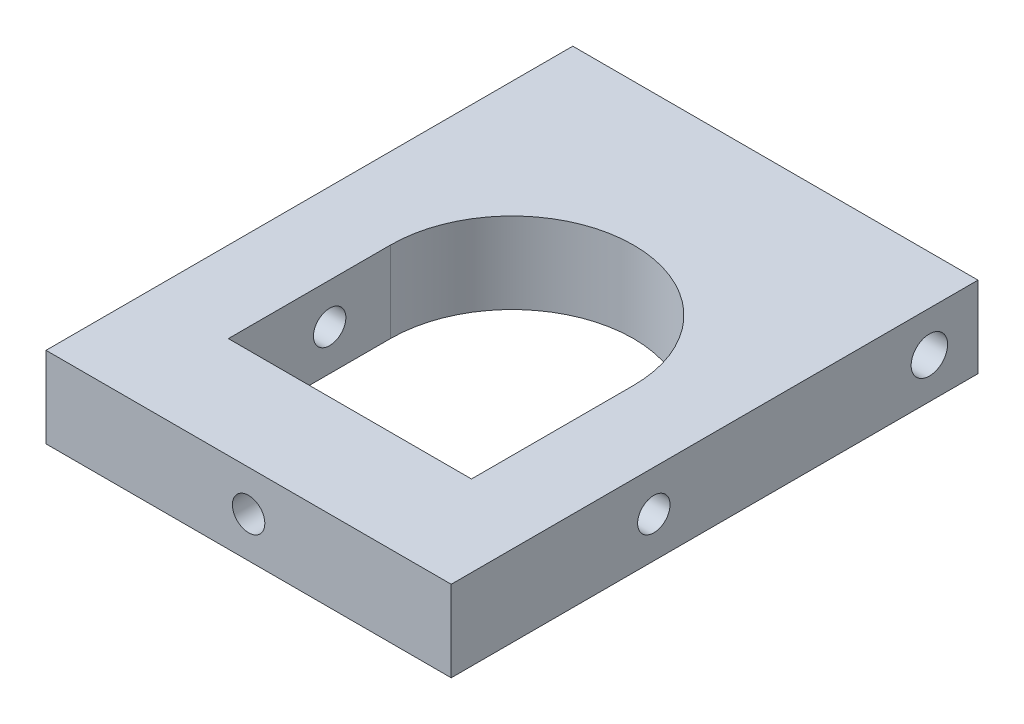
SolidWorks part; units mm, degrees
ref_plane "Front Plane" through (0, 0, 0) normal (0, 0, 1) x (1, 0, 0)
ref_plane "Top Plane" through (0, 0, 0) normal (0, 1, 0) x (1, 0, 0)
ref_plane "Right Plane" through (0, 0, 0) normal (1, 0, 0) x (0, 0, -1)
sketch "Sketch1" plane through (0, 0, 0) normal (0, 1, 0) x (1, 0, 0)
  line L0 (-15, 0) -> (-15, -20)
  line L1 (-25, 32.5) -> (25, 32.5)
  line L2 (-25, 32.5) -> (-25, -32.5)
  line L3 (-25, -32.5) -> (25, -32.5)
  line L4 (25, 32.5) -> (25, -32.5)
  line L5 (-25, 32.5) -> (25, -32.5) construction
  line L6 (-25, -32.5) -> (25, 32.5) construction
  line L7 (-15, -20) -> (15, -20)
  line L8 (15, -20) -> (15, 0)
  arc A0 (15, 0) -> (-15, 0) centre (0, 0) ccw
  point P0 (0, 0)
  dimension "D3" = 30
  dimension "D1" = 50
  dimension "D2" = 65
  dimension "D4" = 20
extrude "Boss-Extrude1" add sketch "Sketch1" along normal blind 10
sketch "Sketch6" plane through (0, 0, 0) normal (1, 0, 0) x (0, 0, -1)
  line L0 (-32.5, 5) -> (32.5, 5) construction
  line L1 (-32.5, 10) -> (-32.5, 0) construction
  line L2 (32.5, 10) -> (32.5, 0) construction
  circle A0 centre (-7.5, 5) radius 2
  circle A1 centre (26.5, 5) radius 2.25
  dimension "D3" = 4
  dimension "D4" = 4.5
  dimension "D1" = 6
  dimension "D2" = 34
extrude "Cut-Extrude1" cut sketch "Sketch6" against normal through all both and the other way through all
sketch "Sketch7" plane through (0, 0, 0) normal (0, 0, 1) x (1, 0, 0)
  line L0 (0, 0) -> (0, 10) construction
  line L1 (-25, 10) -> (25, 10) construction
  circle A0 centre (0, 5) radius 2
  dimension "D1" = 4
extrude "Cut-Extrude2" cut sketch "Sketch7" along normal through all
sketch "Sketch8" plane through (0, 0, 0) normal (0, 1, 0) x (1, 0, 0)
  line L0 (15, -9.5) -> (25, -9.5) construction
  line L1 (0, -32.5) -> (0, -20) construction
  line L3 (15, -7.5) -> (25, -7.5) construction
  line L4 (21.35, -3.75) -> (18.65, -3.75)
  line L5 (21.35, -3.75) -> (21.35, -11.25)
  line L6 (21.35, -11.25) -> (18.65, -11.25)
  line L7 (18.65, -3.75) -> (18.65, -11.25)
  line L8 (21.35, -3.75) -> (18.65, -11.25) construction
  line L9 (21.35, -11.25) -> (18.65, -3.75) construction
  line L10 (-18.65, -3.75) -> (-21.35, -3.75)
  line L11 (-18.65, -3.75) -> (-18.65, -11.25)
  line L12 (-18.65, -11.25) -> (-21.35, -11.25)
  line L17 (25, -32.5) -> (25, 32.5) construction
  line L19 (-21.35, -3.75) -> (-21.35, -11.25)
  line L20 (-18.65, -3.75) -> (-21.35, -11.25) construction
  line L21 (-18.65, -11.25) -> (-21.35, -3.75) construction
  line L22 (3.75, -24.9) -> (-3.75, -24.9)
  line L23 (3.75, -24.9) -> (3.75, -27.6)
  line L24 (3.75, -27.6) -> (-3.75, -27.6)
  line L25 (-3.75, -24.9) -> (-3.75, -27.6)
  line L26 (3.75, -24.9) -> (-3.75, -27.6) construction
  line L27 (3.75, -27.6) -> (-3.75, -24.9) construction
  line L28 (15, -20) -> (15, 0) construction
  line L29 (25, -5.5) -> (15, -5.5) construction
  line L32 (-15, -7.5) -> (-25, -7.5) construction
  line L33 (-15, 0) -> (-15, -20) construction
  line L34 (-25, 32.5) -> (-25, -32.5) construction
  line L35 (-25, -9.5) -> (-15, -9.5) construction
  line L36 (-15, -5.5) -> (-25, -5.5) construction
  line L39 (-25, -32.5) -> (25, -32.5) construction
  line L40 (-15, -20) -> (15, -20) construction
  point P4 (20, -7.5)
  point P9 (-20, -7.5)
  point P22 (0, -26.25)
  dimension "D1" = 2.7
  dimension "D2" = 7.5
extrude "Cut-Extrude3" cut sketch "Sketch8" along normal blind 8.75
equation "\"a\"= 15"
equation "\"b\"= 20"
equation "\"c\"= 10"
equation "\"D1@Boss-Extrude1\"=\"c\""
equation "\"D1@Cut-Extrude3\"=\"c\"/2+3.75"
